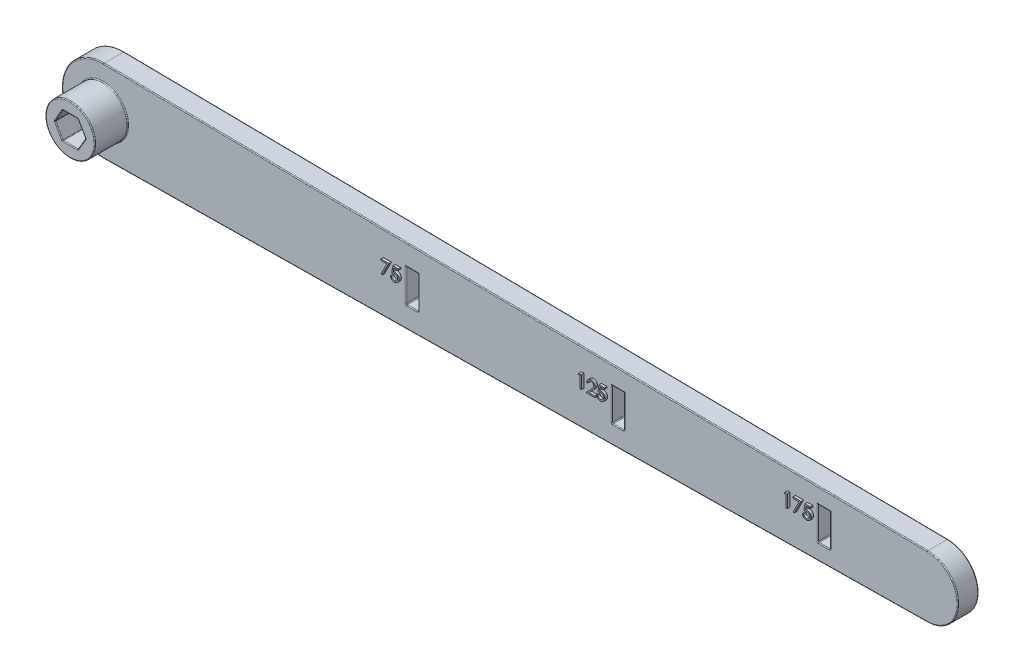
SolidWorks part; units mm, degrees
ref_plane "Front Plane" through (0, 0, 0) normal (0, 0, 1) x (1, 0, 0)
ref_plane "Top Plane" through (0, 0, 0) normal (0, 1, 0) x (1, 0, 0)
ref_plane "Right Plane" through (0, 0, 0) normal (1, 0, 0) x (0, 0, -1)
sketch "Sketch3" plane through (0, 0, 0) normal (0, 0, 1) x (1, 0, 0)
  line L0 (0.125, 9.9992) -> (200.0938, 7.4994)
  line L1 (200.0938, -7.4994) -> (0.125, -9.9992)
  arc A0 (0.125, 9.9992) -> (0.125, -9.9992) centre (0, 0) ccw
  arc A1 (200.0938, -7.4994) -> (200.0938, 7.4994) centre (200, 0) ccw
  dimension "D1" = 20
  dimension "D2" = 15
  dimension "D3" = 200
extrude "Boss-Extrude1" add sketch "Sketch3" along normal blind 5
sketch "Sketch2" plane through (0, 0, 0) normal (0, 0, 1) x (1, 0, 0)
  line L2 (3.695, 0) -> (1.8475, 3.2)
  line L3 (1.8475, 3.2) -> (-1.8475, 3.2)
  line L4 (-1.8475, 3.2) -> (-3.695, 0)
  line L5 (-3.695, 0) -> (-1.8475, -3.2)
  line L6 (-1.8475, -3.2) -> (1.8475, -3.2)
  line L7 (1.8475, -3.2) -> (3.695, 0)
  circle A1 centre (0, 0) radius 3.2 construction
  dimension "D1" = 6.4
extrude "Cut-Extrude2" cut sketch "Sketch2" along normal up to next
sketch "Sketch4" plane through (0, 0, 5) normal (0, 0, 1) x (1, 0, 0)
  line L1 (173.5, 4) -> (176.5, 4)
  line L2 (173.5, 4) -> (173.5, -4)
  line L3 (173.5, -4) -> (176.5, -4)
  line L4 (176.5, 4) -> (176.5, -4)
  line L5 (175, -4) -> (175, 4) construction
  line L6 (0, 0) -> (207.5, 0) construction
  line L7 (123.5, 4) -> (126.5, 4)
  line L8 (123.5, 4) -> (123.5, -4)
  line L9 (123.5, -4) -> (126.5, -4)
  line L10 (126.5, 4) -> (126.5, -4)
  line L11 (125, -4) -> (125, 4) construction
  line L12 (73.5, 4) -> (76.5, 4)
  line L13 (73.5, 4) -> (73.5, -4)
  line L14 (73.5, -4) -> (76.5, -4)
  line L15 (76.5, 4) -> (76.5, -4)
  line L16 (75, -4) -> (75, 4) construction
  arc A0 (200.0938, -7.4994) -> (200.0938, 7.4994) centre (200, 0) ccw construction
  point P4 (175, 0)
  point P33 (75, 0)
  point P34 (125, 0)
  dimension "D1" = 8
  dimension "D3" = 3
  dimension "D4" = 75
  dimension "D5" = 125
  dimension "D6" = 175
extrude "Cut-Extrude3" cut sketch "Sketch4" against normal up to next
sketch "Sketch6" plane through (0, 0, 5) normal (0, 0, 1) x (1, 0, 0)
  line L1 (3.695, 0) -> (1.8475, 3.2) construction
  line L2 (3.695, 0) -> (1.8475, 3.2)
  line L3 (1.8475, 3.2) -> (-1.8475, 3.2)
  line L4 (-1.8475, 3.2) -> (-3.695, 0)
  line L5 (-3.695, 0) -> (-1.8475, -3.2)
  line L6 (-1.8475, -3.2) -> (1.8475, -3.2)
  line L7 (1.8475, -3.2) -> (3.695, 0)
  circle A0 centre (0, 0) radius 6
  circle A2 centre (0, 0) radius 3.2 construction
  dimension "D1" = 12
extrude "Boss-Extrude3" add sketch "Sketch6" along normal blind 8
fillet "Fillet1" radius 0.2 58 edges at (76.5, -4, 2.5) (73.5, -4, 2.5) (176.5, -4, 2.5) (173.5, -4, 2.5) (126.5, -4, 2.5) (123.5, -4, 2.5) (126.5, 0, 0) (125, -4, 0) (123.5, 0, 0) (100.1094, 8.7493, 0) (76.5, 0, 0) (75, -4, 0) (73.5, 0, 0) (-10, 0, 0) (100.1094, -8.7493, 0) (207.5, 0, 0) (176.5, 0, 0) (175, -4, 0) (173.5, 0, 0) (175, -4, 5) (176.5, 0, 5) (100.1094, 8.7493, 5) (207.5, 0, 5) (100.1094, -8.7493, 5) (-10, 0, 5) (73.5, 0, 5) (75, -4, 5) (76.5, 0, 5) (123.5, 0, 5) (125, -4, 5) (126.5, 0, 5) (173.5, 0, 5) (6, 0, 5) (6, 0, 13) (75, 4, 0) (125, 4, 0) (175, 4, 0) (175, 4, 5) (125, 4, 5) (75, 4, 5) (0, -3.2, 0) (-2.7713, -1.6, 0) (-2.7713, 1.6, 0) (0, 3.2, 0) (2.7713, 1.6, 0) (2.7713, -1.6, 0) (2.7713, 1.6, 13) (0, -3.2, 13) (-2.7713, 1.6, 13) (3.695, 0, 6.5) (2.7713, -1.6, 13) (1.8475, -3.2, 6.5) (-1.8475, 3.2, 6.5) (0, 3.2, 13) (1.8475, 3.2, 6.5) (-1.8475, -3.2, 6.5) (-2.7713, -1.6, 13) (-3.695, 0, 6.5)
sketch "Sketch5" plane through (0, 0, 5) normal (0, 0, 1) x (1, 0, 0)
  line L0 (0, 0) -> (207.3, 0) construction
  line L1 (73.5, 4) -> (73.5, -3.8) construction
  line L2 (123.5, 4) -> (123.5, -3.8) construction
  line L3 (173.5, 4) -> (173.5, -3.8) construction
  arc A0 (200.0913, -7.2994) -> (200.0913, 7.2994) centre (200, 0) ccw construction
  text T0 "75"
  text T1 "125"
  text T2 "175\r\n"
  dimension "D1" = 5.8
  dimension "D2" = 8.2
  dimension "D3" = 8.2
extrude "Boss-Extrude2" add sketch "Sketch5" along normal blind 0.6
